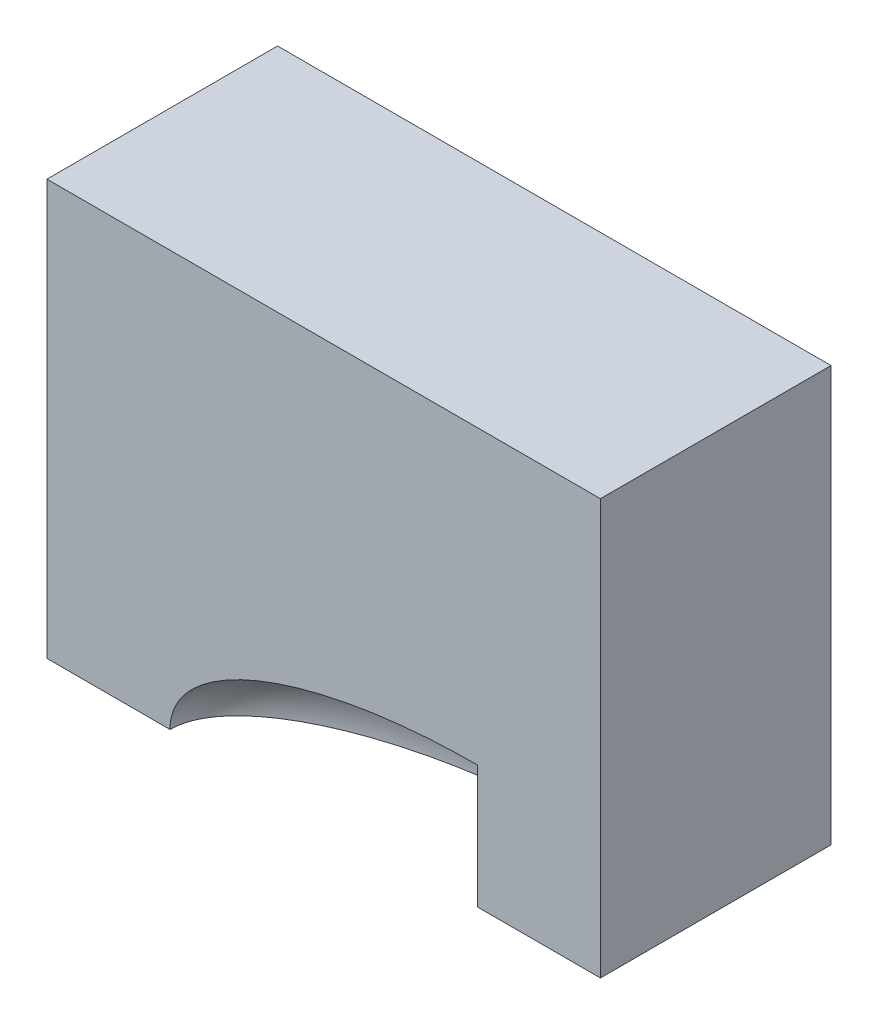
SolidWorks part; units mm, degrees
ref_plane "Front Plane" through (0, 0, 0) normal (0, 0, 1) x (1, 0, 0)
ref_plane "Top Plane" through (0, 0, 0) normal (0, 1, 0) x (1, 0, 0)
ref_plane "Right Plane" through (0, 0, 0) normal (1, 0, 0) x (0, 0, -1)
sketch "Sketch1" plane through (0, 0, 0) normal (0, 0, 1) x (1, 0, 0)
  line L1 (0, 0) -> (91.44, 0)
  line L2 (0, 0) -> (0, 68.58)
  line L3 (0, 68.58) -> (91.44, 68.58)
  line L4 (91.44, 0) -> (91.44, 68.58)
  dimension "D1" = 68.58
  dimension "D2" = 91.44
extrude "Boss-Extrude1" add sketch "Sketch1" along normal blind 38.1
sketch "Sketch4" plane through (0, 0, 0) normal (0, -1, 0) x (-1, 0, 0)
  line L0 (0, -38.1) -> (-91.44, -38.1) construction
  line L1 (-71.12, -38.1) -> (-71.12, -17.78)
  line L2 (-71.12, -38.1) -> (-20.32, -38.1)
  ellipse E0 centre (-71.12, -38.1) end of major axis (-121.92, -38.1) minor radius 20.32 (-20.32, -38.1) -> (-71.12, -17.78) ccw
  dimension "D1" = 20.32
  dimension "D2" = 20.32
  dimension "D3" = 20.32
revolve "Cut-Revolve2" cut sketch "Sketch4" angle 360 about L2
